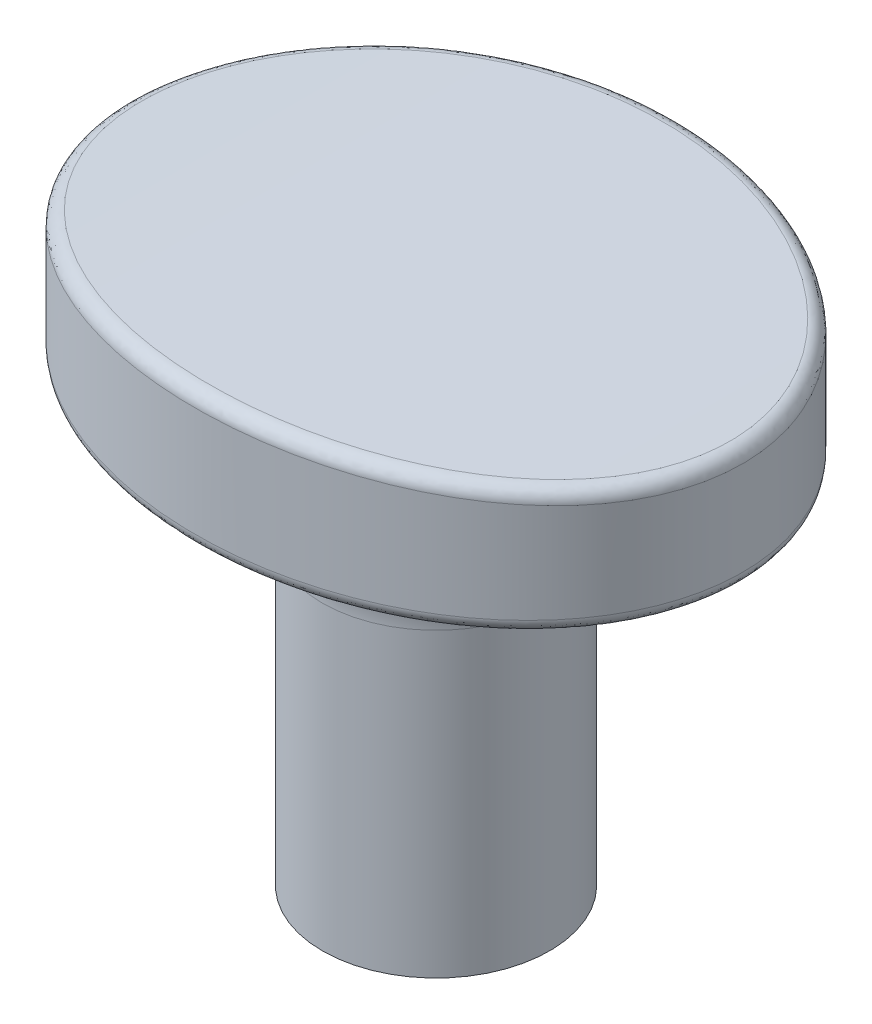
SolidWorks part; units mm, degrees
ref_plane "Front Plane" through (0, 0, 0) normal (0, 0, 1) x (1, 0, 0)
ref_plane "Top Plane" through (0, 0, 0) normal (0, 1, 0) x (1, 0, 0)
ref_plane "Right Plane" through (0, 0, 0) normal (1, 0, 0) x (0, 0, -1)
sketch "Sketch3" plane through (0, 0, 0) normal (0, 1, 0) x (1, 0, 0)
  ellipse E0 centre (0, 0) end of major axis (28.448, 0) minor radius 22.352
extrude "Boss-Extrude1" add sketch "Sketch3" against normal blind 12.7
sketch "Sketch4" plane through (0, 0, 0) normal (0, 0, 1) x (1, 0, 0)
  line L0 (0, 0) -> (0, -6.35) construction
  line L1 (0, -6.35) -> (-28.448, -6.35) construction
  line L2 (-28.448, 0) -> (-28.448, -12.7) construction
  line L6 (0, -6.35) -> (-57.0162, -6.35) construction
  line L10 (-57.0162, -6.35) -> (-57.0162, 0)
  line L11 (-57.0162, 0) -> (0, 0)
  arc A1 (0, 0) -> (-57.0162, -6.35) centre (0, -259.1471) ccw
  dimension "D2" = 259.1471
  dimension "D1" = 6.35
extrude "Cut-Extrude3" cut sketch "Sketch4" against normal through all both and the other way through all
sketch "Sketch5" plane through (0, 0, 0) normal (0, 0, 1) x (1, 0, 0)
  line L0 (0, 0) -> (0, -6.35) construction
  line L1 (0, -6.35) -> (57.0162, -6.35) construction
  line L3 (57.0162, -6.35) -> (57.0162, 0)
  line L4 (57.0162, 0) -> (0, 0)
  arc A0 (0, 0) -> (57.0162, -6.35) centre (0, -259.1471) cw
  dimension "D1" = 6.35
  dimension "D2" = 57.0162
extrude "Cut-Extrude4" cut sketch "Sketch5" against normal through all both and the other way through all
ref_plane "Plane1" through (0, -50.8, 0) normal (0, 1, 0) x (1, 0, 0)
sketch "Sketch6" plane through (0, -50.8, 0) normal (0, 1, 0) x (1, 0, 0)
  circle A0 centre (0, 0) radius 10.541
  dimension "D1" = 21.082
extrude "Boss-Extrude2" add sketch "Sketch6" along normal blind 42.418
fillet "Fillet2" radius 1.27 1 edges at (4.3906, -0.0372, 22.0842)
fillet "Fillet3" radius 1.27 1 edges at (28.448, -12.7, 0)
sketch "Sketch8" plane through (0, -50.8, 0) normal (0, 1, 0) x (1, 0, 0)
  line L0 (0, 0) -> (3.81, 0) construction
  line L1 (3.81, 0) -> (3.81, 3.81) construction
  line L2 (3.81, 3.81) -> (-3.81, 3.81)
  line L3 (-3.81, 3.81) -> (-3.81, -3.81)
  line L4 (-3.81, -3.81) -> (3.81, -3.81)
  line L5 (3.81, -3.81) -> (3.81, 3.81)
  dimension "D1" = 3.81
  dimension "D2" = 3.81
  dimension "D3" = 7.62
  dimension "D4" = 7.62
  dimension "D5" = 7.62
sketch "Sketch9" plane through (0, 0, 0) normal (1, 0, 0) x (0, 0, -1)
  line L0 (0, 0) -> (0, -44.45) construction
  circle A0 centre (0, -44.45) radius 3.81
  dimension "D2" = 7.62
  dimension "D1" = 44.45
fillet "Fillet4" radius 10.16 1 edges at (0, -12.7, 10.541)
extrude "Cut-Extrude7" cut sketch "Sketch8" along normal blind 40.64
extrude "Cut-Extrude8" cut sketch "Sketch9" against normal blind 40.64
